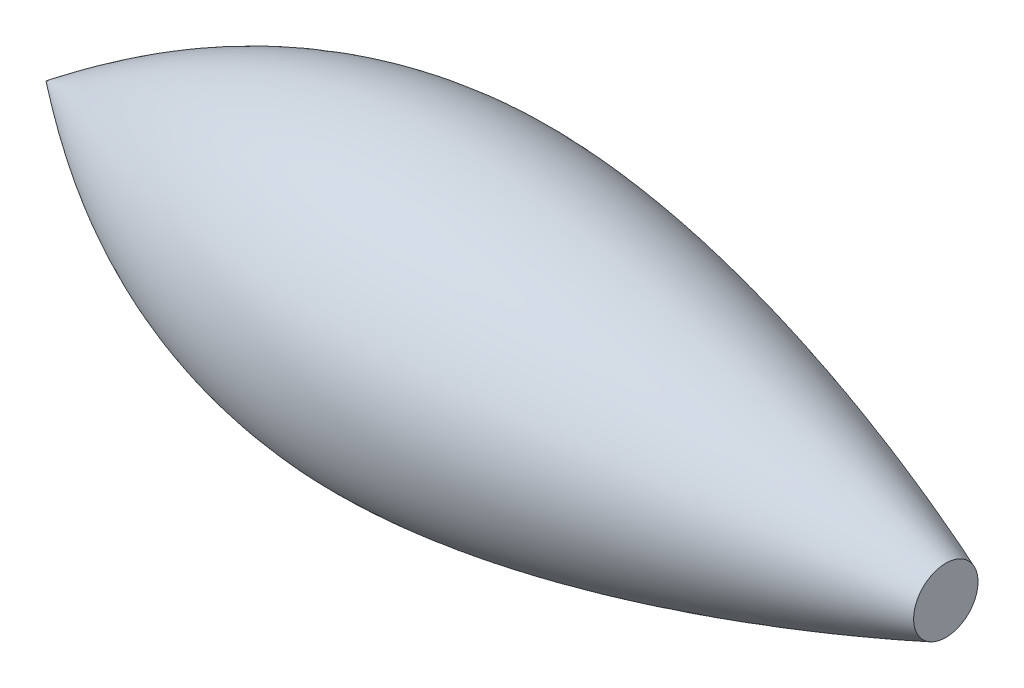
SolidWorks part; units mm, degrees
ref_plane "Front Plane" through (0, 0, 0) normal (0, 0, 1) x (1, 0, 0)
ref_plane "Top Plane" through (0, 0, 0) normal (0, 1, 0) x (1, 0, 0)
ref_plane "Right Plane" through (0, 0, 0) normal (1, 0, 0) x (0, 0, -1)
sketch "Sketch1" plane through (0, 0, 0) normal (0, 0, 1) x (1, 0, 0)
  line L0 (0, 0) -> (5.9859, 0) construction
  line L1 (5.9859, 0) -> (5.9859, 0.2142)
  line L2 (0, 0) -> (5.9859, 0)
  spline S0 degree 3 poles (0, 0) (0.5393, 0.4103) (2.1771, 1.5201) (5.1751, 0.5357) (5.9859, 0.2142) knots 0 0 0 0 0.517109 1 1 1 1
  point P4 (2.5969, 0.9981)
  point P6 (0.2902, 0.2117)
revolve "Revolve1" add sketch "Sketch1" angle 360 about L0
scale "Scale1" [suppressed]
scale "Scale2" bodies to scale 101 scale about origin uniform scaling yes scale factor 692.7273
